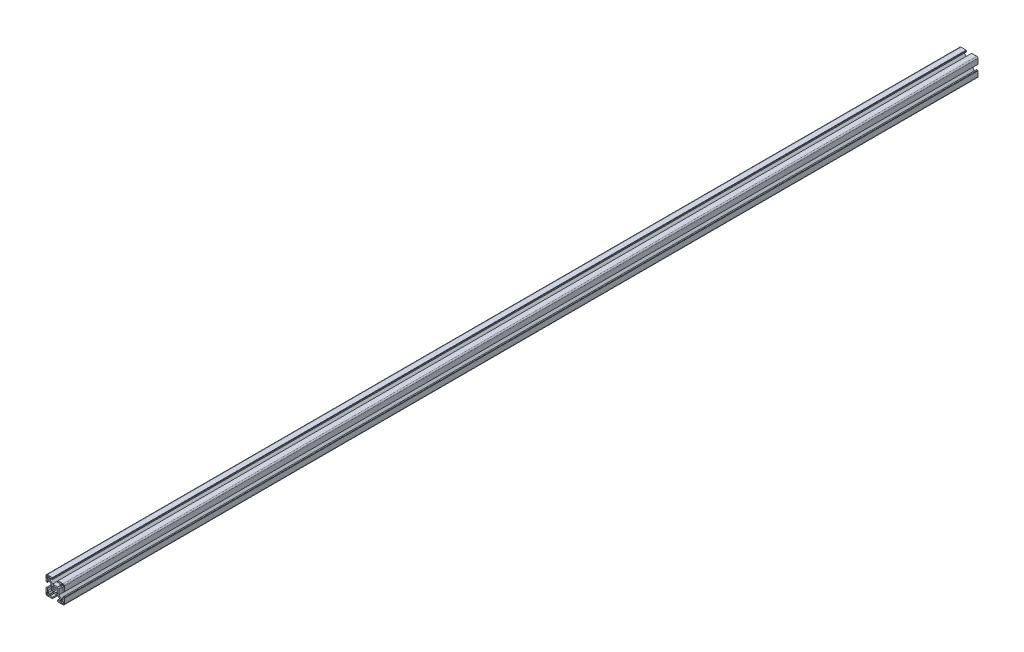
SolidWorks part; units mm, degrees
ref_plane "Front Plane" through (0, 0, 0) normal (0, 0, 1) x (1, 0, 0)
ref_plane "Top Plane" through (0, 0, 0) normal (0, 1, 0) x (1, 0, 0)
ref_plane "Right Plane" through (0, 0, 0) normal (1, 0, 0) x (0, 0, -1)
sketch "Sketch1" plane through (0, 0, 0) normal (0, 0, 1) x (1, 0, 0)
  line L0 (-15, 0) -> (15, 0) construction
  line L1 (0, -15) -> (0, 15) construction
  line L2 (-4.5, 15) -> (4.5, 15) construction
  line L3 (-4, -15) -> (4, -15) construction
  line L4 (-4.5, 15) -> (-4.5, 14.5)
  line L5 (-4.5, 14.5) -> (-4, 14.5)
  line L6 (-4, 14.5) -> (-4, 12.71)
  line L7 (-4, 12.71) -> (-8.2, 12.71)
  line L8 (-8.2, 12.71) -> (-8.2, 9.9961)
  line L9 (-8.2, 9.9961) -> (-4.2039, 6)
  line L10 (-4.2039, 6) -> (0, 6)
  line L11 (0, 0) -> (-15, 15) construction
  line L12 (-4.5, 15) -> (-12.968, 15)
  line L13 (-4.4937, 3.1431) -> (-3.1431, 4.4937)
  line L14 (-13.47, 9.79) -> (-9.79, 9.79)
  line L15 (-13.47, 9.79) -> (-13.47, 13.47)
  line L16 (-13.47, 13.47) -> (-9.79, 13.47)
  line L17 (-9.79, 9.79) -> (-9.79, 13.47)
  line L18 (-13.47, 9.79) -> (-9.79, 13.47) construction
  line L19 (-13.47, 13.47) -> (-9.79, 9.79) construction
  line L20 (-3.1431, 4.4937) -> (-1.7057, 3.0563)
  line L21 (-4.4937, 3.1431) -> (-3.0563, 1.7057)
  line L22 (-6, 4.2039) -> (-6, 0)
  line L23 (-9.9961, 8.2) -> (-6, 4.2039)
  line L24 (-15, 4.5) -> (-15, 12.968)
  line L25 (-12.71, 8.2) -> (-9.9961, 8.2)
  line L26 (-12.71, 4) -> (-12.71, 8.2)
  line L27 (-14.5, 4) -> (-12.71, 4)
  line L28 (-14.5, 4.5) -> (-14.5, 4)
  line L29 (-15, 4.5) -> (-14.5, 4.5)
  circle A0 centre (0, 0) radius 3.5
  arc A1 (-12.968, 15) -> (-15, 12.968) centre (-12.968, 12.968) ccw
  point P4 (0, 0)
  point P8 (0, 0)
  point P13 (0, 15)
  point P15 (0, -15)
  point P16 (0, 6)
  point P23 (-11.63, 11.63)
  point P26 (0, 6)
  point P33 (-3.8184, 3.8184)
  dimension "Center Hole Diameter" = 7
  dimension "D11" = 2.032
  dimension "Rail Height" = 30
  dimension "Rail Width" = 30
  dimension "T-Slot Width" = 8
  dimension "T-Slot Depth" = 9
  dimension "D1" = 9
  dimension "D2" = 45
  dimension "D3" = 8
  dimension "D4" = 2.29
  dimension "D5" = 16.4
  dimension "D7" = 2.54
  dimension "D6" = 3.37
  dimension "D8" = 3.68
  dimension "D9" = 5.4
  dimension "D10" = 1.91
sketch "Sketch2" plane through (0, 0, 0) normal (1, 0, 0) x (0, 0, -1)
  line L0 (-1219.2, 0) -> (1219.2, 0) construction
  line L2 (0, -15) -> (0, 15) construction
  line L3 (0, -15) -> (0, 15) construction
  line L4 (-1219.2, -15) -> (-1219.2, 15) construction
  line L5 (1219.2, -15) -> (1219.2, 15) construction
  point P0 (-1181.7, 0)
  point P3 (0, 0)
  point P4 (1181.7, 0)
  point P12 (-1219.2, 0)
  point P14 (1219.2, 0)
  dimension "Length" = 2438.4
  dimension "D1" = 37.5
sketch "Sketch3" plane through (0, 0, 0) normal (0, 0, 1) x (1, 0, 0)
  line L0 (-3.1431, 4.4937) -> (-1.7057, 3.0563) construction
  line L1 (-4.4937, 3.1431) -> (-3.1431, 4.4937) construction
  line L2 (-4.4937, 3.1431) -> (-3.0563, 1.7057) construction
  line L4 (-13.47, 9.79) -> (-9.79, 9.79)
  line L5 (-9.79, 9.79) -> (-9.79, 13.47)
  line L6 (-9.79, 13.47) -> (-13.47, 13.47)
  line L7 (-13.47, 13.47) -> (-13.47, 9.79)
  line L8 (-13.47, 9.79) -> (-9.79, 9.79)
  line L9 (-9.79, 9.79) -> (-9.79, 13.47)
  line L10 (-9.79, 13.47) -> (-13.47, 13.47)
  line L11 (-13.47, 13.47) -> (-13.47, 9.79)
  line L12 (-4.2039, 6) -> (0, 6) construction
  line L13 (-8.2, 9.9961) -> (-4.2039, 6) construction
  line L14 (-8.2, 12.71) -> (-8.2, 9.9961) construction
  line L15 (-4, 12.71) -> (-8.2, 12.71) construction
  line L16 (-4, 14.5) -> (-4, 12.71) construction
  line L17 (-4.5, 14.5) -> (-4, 14.5) construction
  line L18 (-4.5, 15) -> (-4.5, 14.5) construction
  line L19 (-4.5, 15) -> (-12.968, 15) construction
  line L20 (-15, 4.5) -> (-15, 12.968) construction
  line L21 (-15, 4.5) -> (-14.5, 4.5) construction
  line L22 (-14.5, 4.5) -> (-14.5, 4) construction
  line L23 (-14.5, 4) -> (-12.71, 4) construction
  line L24 (-12.71, 4) -> (-12.71, 8.2) construction
  line L25 (-12.71, 8.2) -> (-9.9961, 8.2) construction
  line L26 (-9.9961, 8.2) -> (-6, 4.2039) construction
  line L27 (-6, 4.2039) -> (-6, 0) construction
  line L28 (-3.1431, 4.4937) -> (-1.7057, 3.0563)
  line L29 (-4.4937, 3.1431) -> (-3.1431, 4.4937)
  line L30 (-4.4937, 3.1431) -> (-3.0563, 1.7057)
  line L32 (-4.2039, 6) -> (0, 6)
  line L33 (-8.2, 9.9961) -> (-4.2039, 6)
  line L34 (-8.2, 12.71) -> (-8.2, 9.9961)
  line L35 (-4, 12.71) -> (-8.2, 12.71)
  line L36 (-4, 14.5) -> (-4, 12.71)
  line L37 (-4.5, 14.5) -> (-4, 14.5)
  line L38 (-4.5, 15) -> (-4.5, 14.5)
  line L39 (-4.5, 15) -> (-12.968, 15)
  line L40 (-15, 4.5) -> (-15, 12.968)
  line L41 (-15, 4.5) -> (-14.5, 4.5)
  line L42 (-14.5, 4.5) -> (-14.5, 4)
  line L43 (-14.5, 4) -> (-12.71, 4)
  line L44 (-12.71, 4) -> (-12.71, 8.2)
  line L45 (-12.71, 8.2) -> (-9.9961, 8.2)
  line L46 (-9.9961, 8.2) -> (-6, 4.2039)
  line L47 (-6, 4.2039) -> (-6, 0)
  line L48 (9.79, 13.47) -> (9.79, 9.79)
  line L49 (9.79, 9.79) -> (13.47, 9.79)
  line L50 (13.47, 9.79) -> (13.47, 13.47)
  line L51 (13.47, 13.47) -> (9.79, 13.47)
  line L52 (4.4937, 3.1431) -> (3.0563, 1.7057)
  line L53 (3.1431, 4.4937) -> (4.4937, 3.1431)
  line L54 (3.1431, 4.4937) -> (1.7057, 3.0563)
  line L55 (6, 4.2039) -> (6, 0)
  line L56 (9.9961, 8.2) -> (6, 4.2039)
  line L57 (12.71, 8.2) -> (9.9961, 8.2)
  line L58 (12.71, 4) -> (12.71, 8.2)
  line L59 (14.5, 4) -> (12.71, 4)
  line L60 (14.5, 4.5) -> (14.5, 4)
  line L61 (15, 4.5) -> (14.5, 4.5)
  line L62 (15, 4.5) -> (15, 12.968)
  line L63 (4.5, 15) -> (12.968, 15)
  line L64 (4.5, 15) -> (4.5, 14.5)
  line L65 (4.5, 14.5) -> (4, 14.5)
  line L66 (4, 14.5) -> (4, 12.71)
  line L67 (4, 12.71) -> (8.2, 12.71)
  line L68 (8.2, 12.71) -> (8.2, 9.9961)
  line L69 (8.2, 9.9961) -> (4.2039, 6)
  line L70 (4.2039, 6) -> (0, 6)
  line L71 (13.47, -9.79) -> (9.79, -9.79)
  line L72 (9.79, -9.79) -> (9.79, -13.47)
  line L73 (9.79, -13.47) -> (13.47, -13.47)
  line L74 (13.47, -13.47) -> (13.47, -9.79)
  line L75 (3.1431, -4.4937) -> (1.7057, -3.0563)
  line L76 (4.4937, -3.1431) -> (3.1431, -4.4937)
  line L77 (4.4937, -3.1431) -> (3.0563, -1.7057)
  line L78 (4.2039, -6) -> (0, -6)
  line L79 (8.2, -9.9961) -> (4.2039, -6)
  line L80 (8.2, -12.71) -> (8.2, -9.9961)
  line L81 (4, -12.71) -> (8.2, -12.71)
  line L82 (4, -14.5) -> (4, -12.71)
  line L83 (4.5, -14.5) -> (4, -14.5)
  line L84 (4.5, -15) -> (4.5, -14.5)
  line L85 (4.5, -15) -> (12.968, -15)
  line L86 (15, -4.5) -> (15, -12.968)
  line L87 (15, -4.5) -> (14.5, -4.5)
  line L88 (14.5, -4.5) -> (14.5, -4)
  line L89 (14.5, -4) -> (12.71, -4)
  line L90 (12.71, -4) -> (12.71, -8.2)
  line L91 (12.71, -8.2) -> (9.9961, -8.2)
  line L92 (9.9961, -8.2) -> (6, -4.2039)
  line L93 (6, -4.2039) -> (6, 0)
  line L94 (-9.79, -13.47) -> (-9.79, -9.79)
  line L95 (-9.79, -9.79) -> (-13.47, -9.79)
  line L96 (-13.47, -9.79) -> (-13.47, -13.47)
  line L97 (-13.47, -13.47) -> (-9.79, -13.47)
  line L98 (-4.4937, -3.1431) -> (-3.0563, -1.7057)
  line L99 (-3.1431, -4.4937) -> (-4.4937, -3.1431)
  line L100 (-3.1431, -4.4937) -> (-1.7057, -3.0563)
  line L101 (-6, -4.2039) -> (-6, 0)
  line L102 (-9.9961, -8.2) -> (-6, -4.2039)
  line L103 (-12.71, -8.2) -> (-9.9961, -8.2)
  line L104 (-12.71, -4) -> (-12.71, -8.2)
  line L105 (-14.5, -4) -> (-12.71, -4)
  line L106 (-14.5, -4.5) -> (-14.5, -4)
  line L107 (-15, -4.5) -> (-14.5, -4.5)
  line L108 (-15, -4.5) -> (-15, -12.968)
  line L109 (-4.5, -15) -> (-12.968, -15)
  line L110 (-4.5, -15) -> (-4.5, -14.5)
  line L111 (-4.5, -14.5) -> (-4, -14.5)
  line L112 (-4, -14.5) -> (-4, -12.71)
  line L113 (-4, -12.71) -> (-8.2, -12.71)
  line L114 (-8.2, -12.71) -> (-8.2, -9.9961)
  line L115 (-8.2, -9.9961) -> (-4.2039, -6)
  line L116 (-4.2039, -6) -> (0, -6)
  arc A0 (-12.968, 15) -> (-15, 12.968) centre (-12.968, 12.968) ccw construction
  circle A1 centre (0, 0) radius 3.5
  arc A2 (-3.0563, 1.7057) -> (-3.0563, -1.7057) centre (0, 0) ccw
  arc A3 (-12.968, 15) -> (-15, 12.968) centre (-12.968, 12.968) ccw
  arc A4 (15, 12.968) -> (12.968, 15) centre (12.968, 12.968) ccw
  arc A5 (12.968, -15) -> (15, -12.968) centre (12.968, -12.968) ccw
  arc A6 (-15, -12.968) -> (-12.968, -15) centre (-12.968, -12.968) ccw
  arc A7 (1.7057, 3.0563) -> (-1.7057, 3.0563) centre (0, 0) ccw
  arc A8 (3.0563, -1.7057) -> (3.0563, 1.7057) centre (0, 0) ccw
  arc A9 (-1.7057, -3.0563) -> (1.7057, -3.0563) centre (0, 0) ccw
  point P116 (0, 0)
  dimension "D1" = 0
  dimension "D2" = 0
  dimension "D3" = 4
extrude "Boss-Extrude1" add sketch "Sketch3" along normal mid plane 2438.4
sketch "Sketch5" plane through (0, 15, 0) normal (0, 1, 0) x (1, 0, 0)
  line L0 (15, -1219.2) -> (15, 1219.2) construction
  line L1 (-15, 1219.2) -> (15, 1219.2)
  line L2 (-15, 1219.2) -> (-15, 280.8)
  line L3 (-15, 280.8) -> (15, 280.8)
  line L4 (15, 1219.2) -> (15, 280.8)
  line L5 (4.2039, -1219.2) -> (-4.2039, -1219.2) construction
  dimension "D1" = 1500
extrude "Cut-Extrude1" cut sketch "Sketch5" against normal through all
equation "\"D1@Sketch2\" = \"Rail Height@Sketch1\" * 1.25"
equation "\"D1@Sketch1\"=\"T-Slot Width@Sketch1\"+1mm"
equation "\"D3@Sketch1\"=\"T-Slot Width@Sketch1\""
equation "\"D1@Boss-Extrude1\"=\"Length@Sketch2\""
